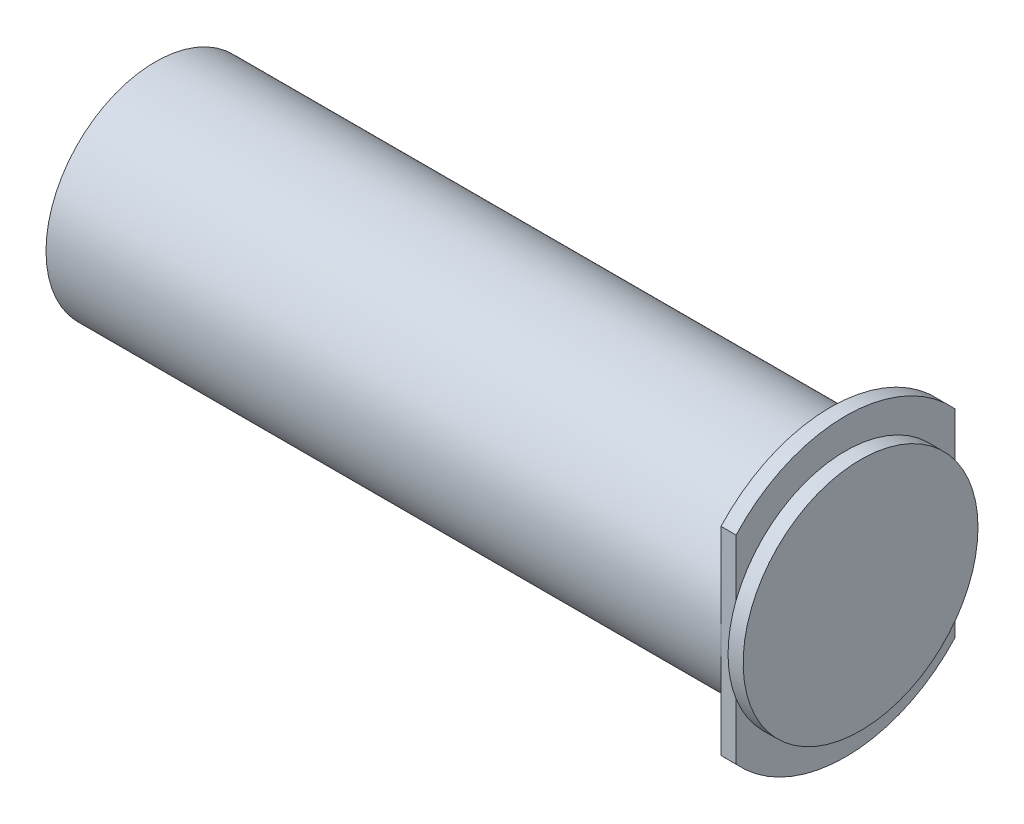
SolidWorks part; units mm, degrees
ref_plane "Płaszczyzna przednia" through (0, 0, 0) normal (0, 0, 1) x (1, 0, 0)
ref_plane "Płaszczyzna górna" through (0, 0, 0) normal (0, 1, 0) x (1, 0, 0)
ref_plane "Płaszczyzna prawa" through (0, 0, 0) normal (1, 0, 0) x (0, 0, -1)
sketch "Sketch1" plane through (0, 0, 0) normal (0, 0, 1) x (1, 0, 0)
  line L0 (-73.8947, 0) -> (76.1053, 0)
  line L1 (-73.8947, 24.31) -> (76.1053, 24.31)
  line L6 (-73.8947, 24.31) -> (-73.8947, 4.825)
  line L7 (76.1053, 24.31) -> (76.1053, 0)
  line L8 (-73.8947, 4.825) -> (-78.8947, 4.825)
  line L9 (-78.8947, 4.825) -> (-78.8947, 0)
  line L10 (-78.8947, 0) -> (-73.8947, 0)
  dimension "D1" = 150
  dimension "D2" = 24.31
  dimension "D3" = 19.485
  dimension "D4" = 5
revolve "Revolve2" add sketch "Sketch1" angle 360 about L0
sketch "Sketch2" plane through (-78.8947, 0, 0) normal (-1, 0, 0) x (0, 0, 1)
  circle A0 centre (0, 0) radius 3.825
  circle A1 centre (0, 0) radius 4.825 construction
  dimension "D1" = 1
extrude "Cut-Extrude1" cut sketch "Sketch2" against normal blind 260 and the other way blind 45
sketch "Sketch3" plane through (76.1053, 0, 0) normal (1, 0, 0) x (0, 0, -1)
  circle A0 centre (0, 0) radius 23.31
  circle A1 centre (0, 0) radius 24.31 construction
  dimension "D1" = 1
extrude "Cut-Extrude2" cut sketch "Sketch3" along a picked direction on the side against the normal blind 149
sketch "Sketch4" plane through (76.1053, 0, 0) normal (1, 0, 0) x (0, 0, -1)
  line L0 (24.31, 0) -> (24.31, 22.0494)
  line L1 (24.31, 22.0494) -> (24.31, -22.0494)
  line L2 (-24.31, 0) -> (-24.31, 22.0494)
  line L3 (-24.31, 22.0494) -> (-24.31, -22.0494)
  circle A0 centre (0, 0) radius 32.82
  circle A1 centre (0, 0) radius 24.31 construction
  circle A2 centre (0, 0) radius 23.31
  circle M1 centre (0, 0) radius 23.31
  circle M2 centre (0, 0) radius 24.31
  dimension "D1" = 65.64
extrude "Boss-Extrude1" add sketch "Sketch4" along normal blind 3.35 separate body contours L0 A0 L2 M2 | L3 A0 L1 M2 | M2 M1
sketch "Sketch6" plane through (79.4553, 0, 0) normal (1, 0, 0) x (0, 0, -1)
  circle A0 centre (0, 0) radius 26.095
  dimension "D1" = 52.19
extrude "Boss-Extrude7" add sketch "Sketch6" along normal blind 3.35
